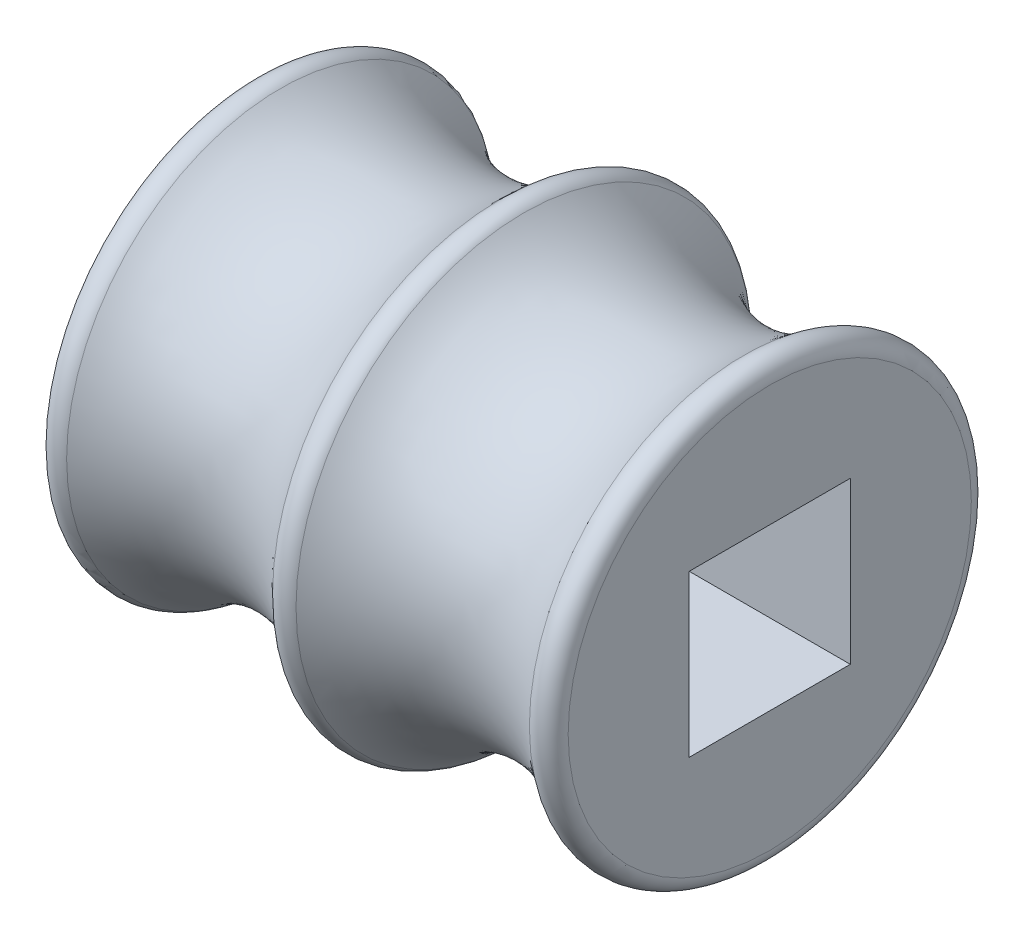
SolidWorks part; units mm, degrees
ref_plane "Front Plane" through (0, 0, 0) normal (0, 0, 1) x (1, 0, 0)
ref_plane "Top Plane" through (0, 0, 0) normal (0, 1, 0) x (1, 0, 0)
ref_plane "Right Plane" through (0, 0, 0) normal (1, 0, 0) x (0, 0, -1)
sketch "Sketch2" plane through (0, 0, 0) normal (0, 0, 1) x (1, 0, 0)
  line L0 (0, 0) -> (10.16, 0) construction
  line L1 (0, 2.286) -> (10.16, 2.286)
  line L2 (10.16, 2.286) -> (10.16, 9.525)
  line L3 (0, 2.286) -> (0, 9.525)
  arc A0 (0, 9.525) -> (10.16, 9.525) centre (5.08, 13.335) ccw
  point P9 (0, 0)
  point P10 (5.08, 2.286)
  point P11 (0, 0)
  point P12 (0, 9.5983)
  dimension "D1" = 12.7
  dimension "D2" = 10.16
  dimension "D3" = 4.572
  dimension "D4" = 19.05
revolve "Revolve1" add sketch "Sketch2" angle 360 about L0
sketch "Sketch3" plane through (10.16, 0, 0) normal (1, 0, 0) x (0, 0, -1)
  line L1 (3.175, -3.175) -> (-3.175, -3.175)
  line L2 (3.175, -3.175) -> (3.175, 3.175)
  line L3 (3.175, 3.175) -> (-3.175, 3.175)
  line L4 (-3.175, -3.175) -> (-3.175, 3.175)
  line L5 (3.175, -3.175) -> (-3.175, 3.175) construction
  line L6 (3.175, 3.175) -> (-3.175, -3.175) construction
  point P0 (0, 0)
  dimension "D1" = 6.35
extrude "Cut-Extrude1" cut sketch "Sketch3" against normal through all
mirror "Mirror1" about plane through (0, 2.286, 0) normal (1, 0, 0) of "Cut-Extrude1", "Revolve1"
fillet "Fillet1" radius 0.635 3 edges at (10.16, 0, 9.525) (-10.16, 0, 9.525) (0, 0, 9.525)
